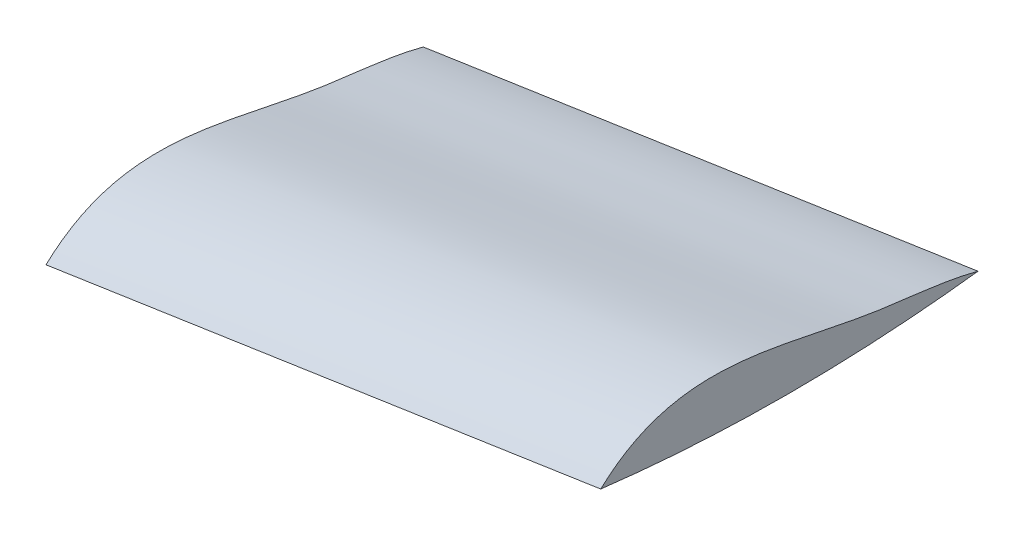
SolidWorks part; units mm, degrees
ref_plane "Front Plane" through (0, 0, 0) normal (0, 0, 1) x (1, 0, 0)
ref_plane "Top Plane" through (0, 0, 0) normal (0, 1, 0) x (1, 0, 0)
ref_plane "Right Plane" through (0, 0, 0) normal (1, 0, 0) x (0, 0, -1)
sketch "Sketch1" plane through (0, 0, 0) normal (1, 0, 0) x (0, 0, -1)
  line L0 (-60.6513, 149.3349) -> (-172.5951, 147.0248) construction
  spline S0 degree 3 poles (-43.701, -3.6751) (60.094, 93.5577) (246.6646, 18.2597) (417.6994, 8.7408) (464.299, -3.6751) knots 0 0 0 0 0.726777 1 1 1 1
  spline S1 degree 2 poles (-43.701, -3.6751) (209.423, -34.3264) (464.299, -3.6751) knots 0 0 0 1 1 1
  point P0 (-43.701, -3.6751)
  point P1 (464.299, -3.6751)
  dimension "D1" = 508
sketch "Sketch2" plane through (0, 0, 0) normal (0, 1, 0) x (1, 0, 0)
  line L0 (0, 157.4919) -> (-635, 45.5243)
  line L1 (0, -43.701) -> (0, 464.299) construction
  line L2 (0, 157.4919) -> (0, -13.3335) construction
  dimension "D1" = 635
  dimension "D2" = 80
sweep "Sweep1" add profiles "Sketch1" path "Sketch2"
sketch "Sketch3" plane through (-635, 0, 0) normal (-1, 0, 0) x (0, 0, 1)
  line L0 (-352.3314, -3.6751) -> (155.6686, -3.6751)
